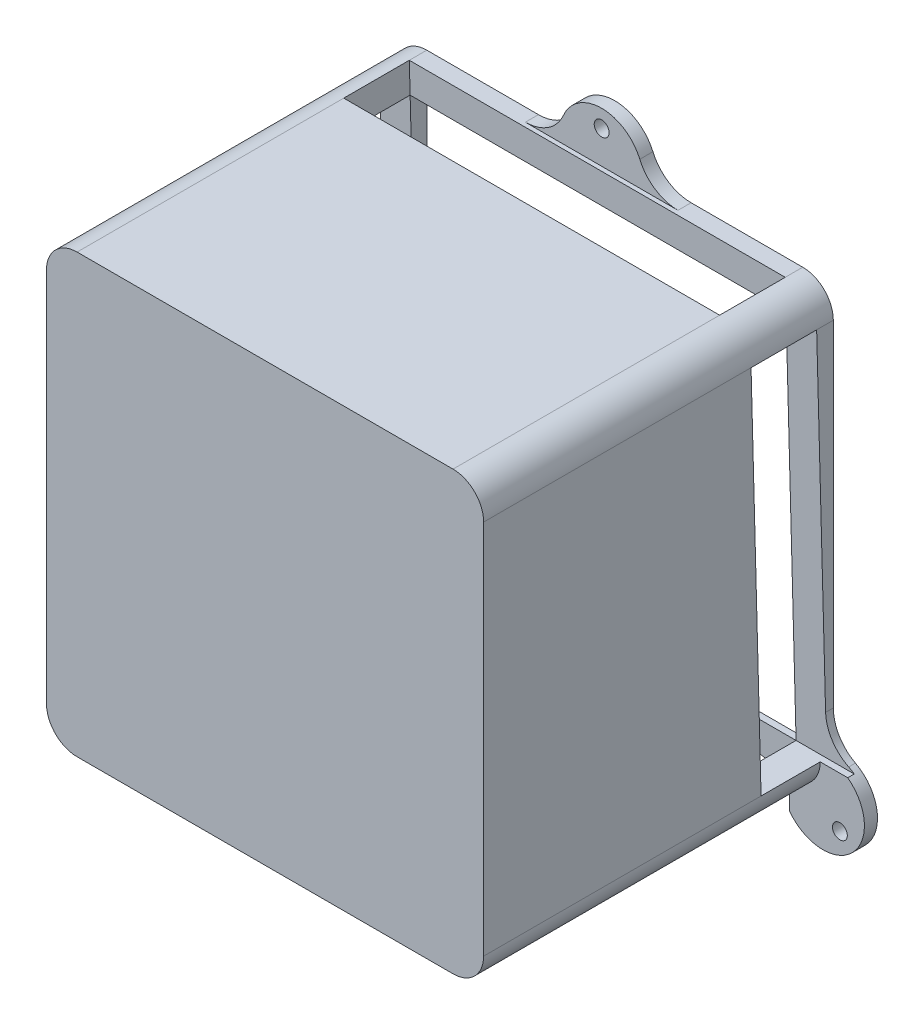
SolidWorks part; units mm, degrees
ref_plane "Plan de face" through (0, 0, 0) normal (0, 0, 1) x (1, 0, 0)
ref_plane "Plan de dessus" through (0, 0, 0) normal (0, 1, 0) x (1, 0, 0)
ref_plane "Plan de droite" through (0, 0, 0) normal (1, 0, 0) x (0, 0, -1)
sketch "Esquisse1" plane through (0, 0, 0) normal (0, 0, 1) x (1, 0, 0)
  line L1 (0, 0) -> (100, 0)
  line L2 (0, 0) -> (0, 100)
  line L3 (0, 100) -> (100, 100)
  line L4 (100, 0) -> (100, 100)
  dimension "D1" = 100
  dimension "D2" = 100
extrude "Boss.-Extru.1" add sketch "Esquisse1" along normal blind 80
sketch "Esquisse2" plane through (0, 0, 0) normal (0, 0, -1) x (-1, 0, 0)
  line L8 (-7, 7) -> (-7, 93)
  line L9 (-7, 93) -> (-93, 93)
  line L10 (-93, 93) -> (-93, 7)
  line L11 (-93, 7) -> (-7, 7)
  line L12 (-7, 7) -> (-7, 93)
  line L13 (-7, 93) -> (-93, 93)
  line L14 (-93, 93) -> (-93, 7)
  line L15 (-93, 7) -> (-7, 7)
  dimension "D1" = 7
extrude "Enlèv. mat.-Extru.1" cut sketch "Esquisse2" against normal offset from surface (70 mm away) 10 up to face at (50, 50, 80)
sketch "Esquisse3" plane through (0, 0, 80) normal (0, 0, 1) x (1, 0, 0)
  line L0 (95, 95) -> (5, 95)
  line L1 (5, 95) -> (5, 5)
  line L2 (5, 5) -> (95, 5)
  line L3 (95, 5) -> (95, 95)
  line L4 (0, 100) -> (0, 0)
  line L5 (0, 0) -> (100, 0)
  line L6 (100, 0) -> (100, 100)
  line L7 (100, 100) -> (0, 100)
  line L8 (0, 100) -> (0, 0)
  line L9 (0, 0) -> (100, 0)
  line L10 (100, 0) -> (100, 100)
  line L11 (100, 100) -> (0, 100)
  dimension "D1" = 0
  dimension "D2" = 5
extrude "Boss.-Extru.2" [suppressed] add sketch "Esquisse3" along normal blind 10
sketch "Esquisse4" plane through (0, 0, 0) normal (0, 0, -1) x (-1, 0, 0)
  line L0 (-93, 7) -> (-116.2207, -16.2207) construction
  line L1 (-7, 7) -> (8.1122, -8.1122) construction
  line L6 (0, 0) -> (-100, 0) construction
  line L7 (3.2972, -11.3596) -> (13.4788, -1.1781) construction
  line L8 (-114.7245, 0.0676) -> (-101.0769, -13.5799) construction
  line L9 (-50, 93) -> (-50, 115.4924) construction
  line L10 (-7, 93) -> (-93, 93) construction
  line L11 (-100, 100) -> (0, 100) construction
  line L12 (-62.0341, 111.5) -> (-40.7837, 111.5) construction
  line L13 (-46.9586, 93) -> (-53.0414, 93)
  circle A0 centre (-104.5, -4.5) radius 1.5
  circle A1 centre (4.5, -4.5) radius 1.5
  circle A2 centre (0.6109, -0.6109) radius 9.5
  circle A3 centre (-100.6109, -0.6109) radius 9.5
  circle A4 centre (-50, 107.5) radius 1.5
  arc A5 (-46.9586, 93) -> (-53.0414, 93) centre (-50, 102) ccw
  point P28 (-50, 100)
  dimension "D1" = 3
  dimension "D4" = 3
  dimension "D7" = 19
  dimension "D8" = 19
  dimension "D10" = 3
  dimension "D12" = 19
  dimension "D2" = 4.5
  dimension "D3" = 4
  dimension "D5" = 4.5
  dimension "D6" = 4
  dimension "D9" = 7.5
  dimension "D11" = 4
extrude "Boss.-Extru.3" add sketch "Esquisse4" against normal blind 3
fillet "Congé1" radius 7 4 edges at (100, 0, 41.5) (0, 100, 40) (0, 0, 41.5) (100, 100, 40)
fillet "Congé3" [suppressed] radius 1
fillet "Congé4" radius 9.5 6 edges at (8.8694, 0, 1.5) (0, 8.8694, 1.5) (91.1306, 0, 1.5) (100, 8.8694, 1.5) (59.2871, 100, 1.5) (40.7129, 100, 1.5)
hole_wizard "Dégagement M31" positions "Esquisse5" profile "Esquisse6" hole size "M3" standard "ISO" end condition up to next
sketch "Esquisse5" plane through (0, 0, 3) normal (0, 0, 1) x (1, 0, 0)
  point P0 (104.5, -4.5)
  point P3 (-4.5, -4.5)
  point P6 (50, 107.5)
sketch "Esquisse6" plane through (104.5, -4.5, 3) normal (1, 0, 0) x (0, -1, 0)
  line L0 (0, 0) -> (0, 3)
  line L1 (0, 3) -> (1.7, 3)
  line L2 (1.7, 3) -> (1.7, 0)
  line L5 (1.7, 0) -> (0, 0)
  line L11 (0, -6.35) -> (0, 107.95) construction
  dimension "Diamètre du perçage jusqu'au prochain" = 3.4
  dimension "Profondeur du perçage jusqu'au prochain" = 3
ref_plane "Plan1" through (0, 100, 0) normal (0, 1, 0) x (1, 0, 0)
ref_plane "Plan2" through (0, 102.0609, 2.7218) normal (0, 0.9996, 0.0267) x (1, 0, 0)
sketch "Esquisse8" plane through (0, 102.0609, 2.7218) normal (0, 0.9996, 0.0267) x (1, 0, 0)
  line L0 (7, 2.6658) -> (7, -77.3057) construction
  line L1 (7, -16.3342) -> (93, -16.3342)
  line L2 (7, -16.3342) -> (7, -1.3342)
  line L3 (7, -1.3342) -> (93, -1.3342)
  line L4 (93, -16.3342) -> (93, -1.3342)
  line L5 (93, -77.3057) -> (93, 2.6658) construction
  line L6 (0, 2.6658) -> (100, 2.6658) construction
  dimension "D1" = 15
  dimension "D2" = 4
extrude "Enlèv. mat.-Extru.2" cut sketch "Esquisse8" against normal offset from surface (108.664 mm away) 7
sketch "Esquisse9" plane through (93, 0, 0) normal (-1, 0, 0) x (0, 0, 1)
  line L0 (18.8201, 93) -> (16.5266, 7)
  line L1 (16.5266, 7) -> (1.5213, 7)
  line L2 (1.5213, 7) -> (3.8147, 93)
  line L3 (3.8147, 93) -> (18.8201, 93)
extrude "Enlèv. mat.-Extru.3" cut sketch "Esquisse9" along normal offset from surface (115 mm away) 7 from offset 15
